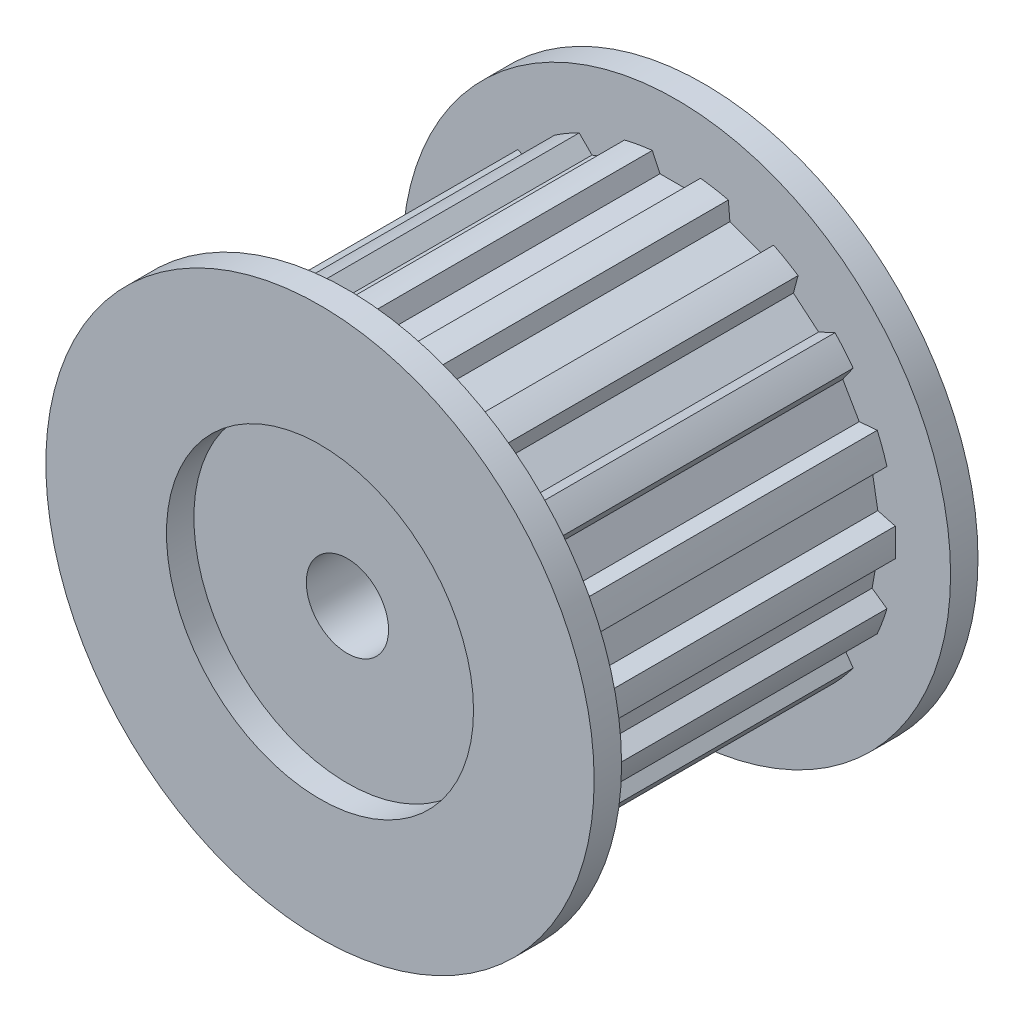
SolidWorks part; units mm, degrees
ref_plane "Plan de face" through (0, 0, 0) normal (0, 0, 1) x (1, 0, 0)
ref_plane "Plan de dessus" through (0, 0, 0) normal (0, 1, 0) x (1, 0, 0)
ref_plane "Plan de droite" through (0, 0, 0) normal (1, 0, 0) x (0, 0, -1)
sketch "Esquisse1" plane through (0, 0, 0) normal (0, 0, 1) x (1, 0, 0)
  circle A0 centre (0, 0) radius 8
  circle A1 centre (0, 0) radius 1.5
  dimension "D1" = 16
  dimension "D2" = 3
extrude "Extrusion1" add sketch "Esquisse1" along normal blind 12
sketch "Esquisse2" plane through (0, 0, 12) normal (0, 0, 1) x (1, 0, 0)
  line L0 (0, 0) -> (0, 16.2125) construction
  line L1 (-0.6, 7.3535) -> (0.6, 7.3535)
  line L2 (0.6, 7.3535) -> (1.0023, 8.2162)
  line L3 (1.0023, 8.2162) -> (-1.0023, 8.2162)
  line L4 (-1.0023, 8.2162) -> (-0.6, 7.3535)
  dimension "D1" = 25
  dimension "D2" = 50
  dimension "D3" = 0.6
  dimension "D4" = 0.6
extrude "Extrusion2" cut sketch "Esquisse2" against normal through all
pattern_circular "Répétition circulaire1" count 18 every 20 about axis through (0, 0, 0) along (0, 0, 1) of "Extrusion2"
sketch "Esquisse3" plane through (0, 0, 12) normal (0, 0, 1) x (1, 0, 0)
  circle A0 centre (0, 0) radius 10
  circle A1 centre (0, 0) radius 5.6
extrude "Extrusion3" add sketch "Esquisse3" along normal blind 1
pattern_linear "Répétition linéaire1" count 2 spacing 13 along (0, 0, -1) of "Extrusion3"
